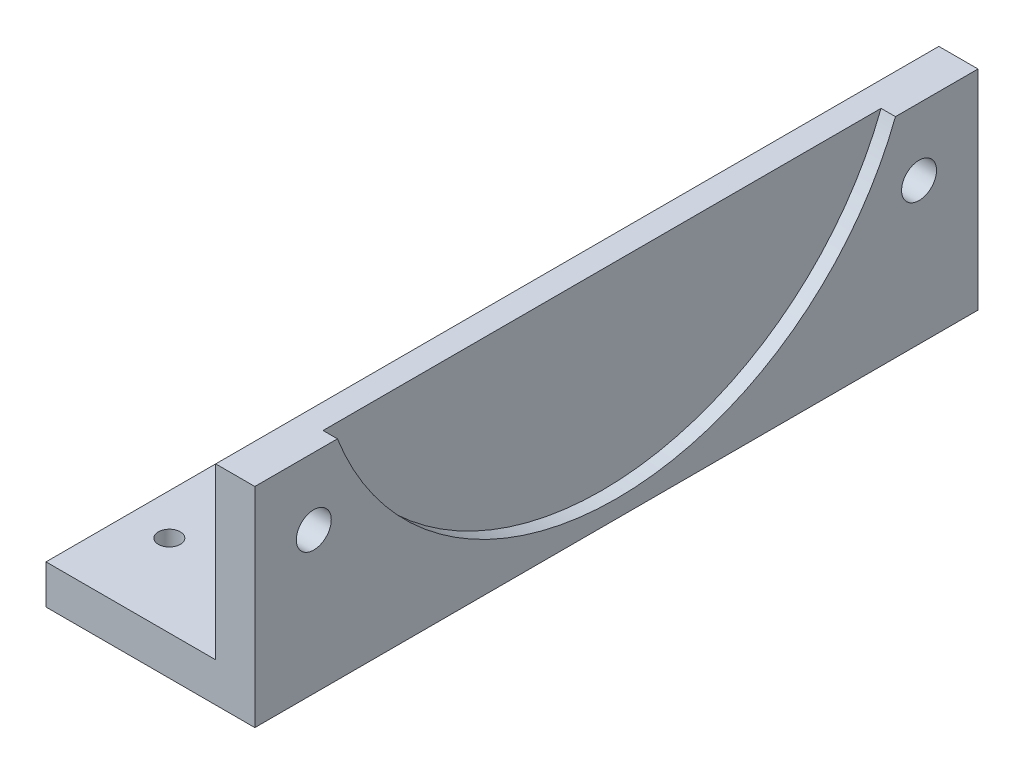
SolidWorks part; units mm, degrees
ref_plane "Front" through (0, 0, 0) normal (0, 0, 1) x (1, 0, 0)
ref_plane "Top" through (0, 0, 0) normal (0, 1, 0) x (1, 0, 0)
ref_plane "Right" through (0, 0, 0) normal (1, 0, 0) x (0, 0, -1)
sketch "Sketch1" plane through (0, 0, 0) normal (0, 0, 1) x (1, 0, 0)
  line L0 (15.875, 15.875) -> (25.4, 25.4) construction
  line L1 (-25.4, -25.4) -> (25.4, -25.4)
  line L2 (-25.4, -25.4) -> (-25.4, -15.875)
  line L3 (15.875, 25.4) -> (25.4, 25.4)
  line L4 (25.4, -25.4) -> (25.4, 25.4)
  line L5 (-25.4, -25.4) -> (-15.875, -15.875) construction
  line L9 (-25.4, -15.875) -> (15.875, -15.875)
  line L10 (15.875, 25.4) -> (15.875, -15.875)
  line L13 (15.875, -15.875) -> (25.4, -25.4) construction
  point P0 (0, 0)
  point P9 (-4.7625, 4.7625)
  dimension "D1" = 50.8
  dimension "D3" = 9.525
extrude "Boss-Extrude1" add sketch "Sketch1" along normal blind 190
sketch "Sketch3" plane through (25.4, 0, 0) normal (1, 0, 0) x (0, 0, -1)
  circle A2 centre (-95, 51.6) radius 72.75
  dimension "D1" = 145.5
extrude "Cut-Extrude3" cut sketch "Sketch3" against normal blind 3.5
sketch "Sketch4" plane through (0, 0, 190) normal (0, 0, 1) x (1, 0, 0)
  line L6 (25.4, -25.4) -> (25.4, 25.4)
  line L7 (25.4, 25.4) -> (15.875, 25.4)
  line L8 (15.875, 25.4) -> (15.875, -15.875)
  line L9 (15.875, -15.875) -> (-25.4, -15.875)
  line L10 (-25.4, -15.875) -> (-25.4, -25.4)
  line L11 (-25.4, -25.4) -> (25.4, -25.4)
  line L12 (25.4, -25.4) -> (25.4, 25.4)
  line L13 (25.4, 25.4) -> (15.875, 25.4)
  line L14 (15.875, 25.4) -> (15.875, -15.875)
  line L15 (15.875, -15.875) -> (-25.4, -15.875)
  line L16 (-25.4, -15.875) -> (-25.4, -25.4)
  line L17 (-25.4, -25.4) -> (25.4, -25.4)
  dimension "D1" = 0
extrude "Cut-Extrude4" cut sketch "Sketch4" against normal blind 7.05
sketch "Sketch5" plane through (0, 0, 0) normal (0, 0, -1) x (-1, 0, 0)
  line L6 (-25.4, 25.4) -> (-25.4, -25.4)
  line L7 (-25.4, -25.4) -> (25.4, -25.4)
  line L8 (25.4, -25.4) -> (25.4, -15.875)
  line L9 (25.4, -15.875) -> (-15.875, -15.875)
  line L10 (-15.875, -15.875) -> (-15.875, 25.4)
  line L11 (-15.875, 25.4) -> (-25.4, 25.4)
  line L12 (-25.4, 25.4) -> (-25.4, -25.4)
  line L13 (-25.4, -25.4) -> (25.4, -25.4)
  line L14 (25.4, -25.4) -> (25.4, -15.875)
  line L15 (25.4, -15.875) -> (-15.875, -15.875)
  line L16 (-15.875, -15.875) -> (-15.875, 25.4)
  line L17 (-15.875, 25.4) -> (-25.4, 25.4)
  dimension "D1" = 0
extrude "Cut-Extrude5" cut sketch "Sketch5" against normal blind 7.05
sketch "Sketch6" plane through (25.4, 0, 0) normal (1, 0, 0) x (0, 0, -1)
  circle A0 centre (-168.6122, 9.1) radius 3.975
  circle A1 centre (-21.3878, 9.1) radius 4.4316
hole_wizard "Tap Drill for M10x1.5 Tap1" positions "3DSketch1" profile "Sketch7" hole size "M10x1.5" standard "ANSI Metric" end condition up to next
sketch3d "3DSketch1"
  point P0 (25.4, 9.1, 168.6122)
  point P3 (25.4, 9.1, 21.3878)
sketch "Sketch7" plane through (25.4, 9.1, 168.6122) normal (0, 1, 0) x (0, 0, -1)
  line L0 (0, 0) -> (0, 9.525)
  line L1 (0, 9.525) -> (4.25, 9.525)
  line L2 (4.25, 9.525) -> (4.25, 0)
  line L5 (4.25, 0) -> (0, 0)
  line L11 (0, -6.35) -> (0, 107.95) construction
  dimension "Thru Hole Dia." = 8.5
  dimension "Thru Hole Depth" = 9.525
sketch "Sketch8" plane through (0, -15.875, 0) normal (0, 1, 0) x (1, 0, 0)
  line L0 (-25.4, -95) -> (15.875, -95) construction
  line L1 (-25.4, -182.95) -> (-25.4, -7.05) construction
  line L2 (15.875, -182.95) -> (15.875, -7.05) construction
  line L3 (-15.4, -7.05) -> (-15.4, -95) construction
  line L4 (-25.4, -7.05) -> (15.875, -7.05) construction
  line L5 (4.6, -7.05) -> (4.6, -95) construction
  circle A0 centre (-15.4, -27.05) radius 2.665
  circle A1 centre (4.6, -95) radius 2.665
  circle A2 centre (-15.4, -162.95) radius 2.665
  dimension "D3" = 20
  dimension "D4" = 5.33
  dimension "D1" = 10
  dimension "D2" = 20
extrude "Cut-Extrude6" cut sketch "Sketch8" against normal up to next
